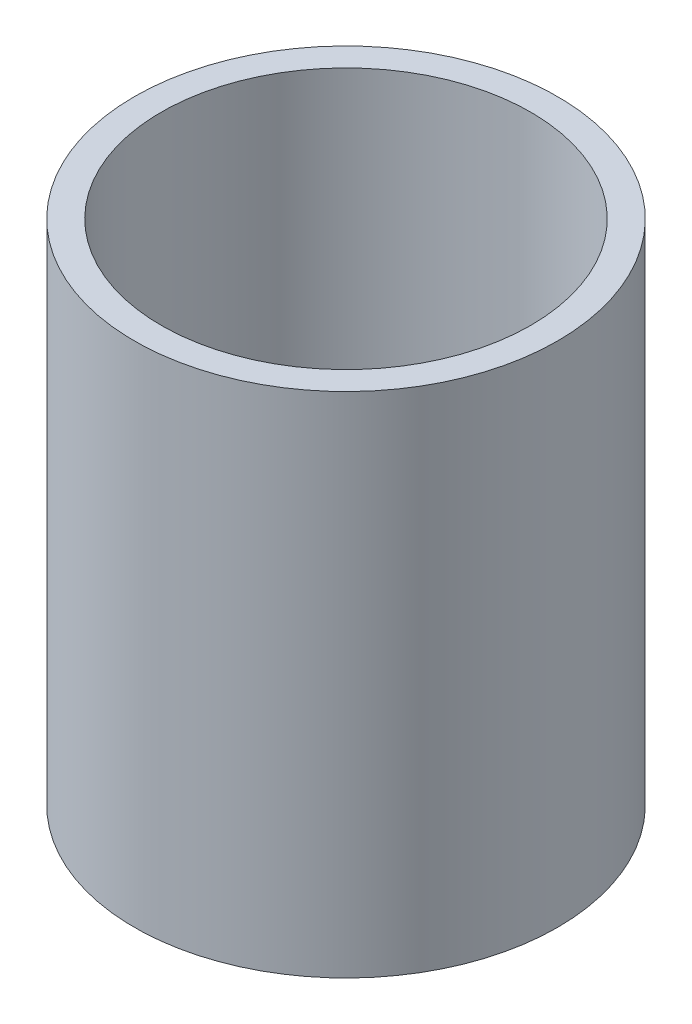
SolidWorks part; units mm, degrees
material "1060 Alloy"
ref_plane "Front Plane" through (0, 0, 0) normal (0, 0, 1) x (1, 0, 0)
ref_plane "Top Plane" through (0, 0, 0) normal (0, 1, 0) x (1, 0, 0)
ref_plane "Right Plane" through (0, 0, 0) normal (1, 0, 0) x (0, 0, -1)
sketch "Sketch2" plane through (0, 0, 0) normal (0, 0, 1) x (1, 0, 0)
  line L0 (12.5, 30) -> (10.9125, 30)
  line L1 (0, 0) -> (12.5, 0)
  line L4 (12.5, 0) -> (12.5, 30)
  line L5 (10.9125, 30) -> (10.9125, 1.5875)
  line L6 (10.9125, 1.5875) -> (0, 1.5875)
  line L7 (0, 1.5875) -> (0, 0)
  line L8 (10.9125, 1.5875) -> (10.9125, 0) construction
  line L9 (10.9125, 1.5875) -> (12.5, 1.5875) construction
  line L10 (0, 0) -> (0, 30) construction
  dimension "D1" = 30
  dimension "D2" = 12.5
  dimension "D3" = 1.5875
revolve "Revolve1" add sketch "Sketch2" angle 360 about L10
